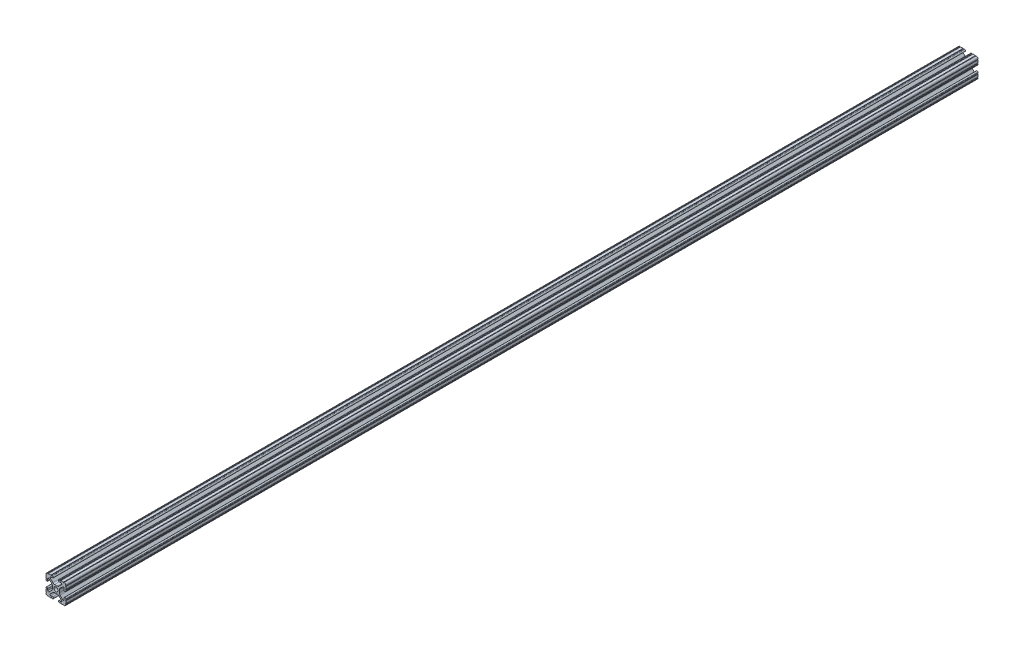
SolidWorks part; units mm, degrees
ref_plane "Front Plane" through (0, 0, 0) normal (0, 0, 1) x (1, 0, 0)
ref_plane "Top Plane" through (0, 0, 0) normal (0, 1, 0) x (1, 0, 0)
ref_plane "Right Plane" through (0, 0, 0) normal (1, 0, 0) x (0, 0, -1)
ref_plane "Plane1" through (0, 0, -2463.8) normal (0, 0, -1) x (-1, 0, 0)
sketch "Sketch1" plane through (0, 0, -2463.8) normal (0, 0, -1) x (-1, 0, 0)
  line L0 (12.7, -9.5504) -> (12.7, -6.3331)
  line L1 (12.7, -5.3171) -> (12.7, -4.3434)
  line L2 (10.4902, -4.3434) -> (10.4902, -6.4748)
  line L3 (8.7558, -7.1932) -> (5.4257, -3.8632)
  line L4 (4.4958, -1.6181) -> (4.4958, 1.6181)
  line L5 (5.4257, 3.8632) -> (8.7558, 7.1932)
  line L6 (10.4902, 6.4748) -> (10.4902, 4.3434)
  line L7 (12.7, 4.3434) -> (12.7, 5.3171)
  line L8 (12.7, 6.3331) -> (12.7, 9.5504)
  line L9 (9.5504, 12.7) -> (6.3331, 12.7)
  line L10 (5.3171, 12.7) -> (4.3434, 12.7)
  line L11 (4.3434, 10.4902) -> (6.4748, 10.4902)
  line L12 (7.1932, 8.7558) -> (3.8632, 5.4257)
  line L13 (1.6181, 4.4958) -> (-1.6181, 4.4958)
  line L14 (-3.8632, 5.4257) -> (-7.1932, 8.7558)
  line L15 (-6.4748, 10.4902) -> (-4.3434, 10.4902)
  line L16 (-4.3434, 12.7) -> (-5.3171, 12.7)
  line L17 (-6.3331, 12.7) -> (-9.5504, 12.7)
  line L18 (-12.7, 9.5504) -> (-12.7, 6.3331)
  line L19 (-12.7, 5.3171) -> (-12.7, 4.3434)
  line L20 (-10.4902, 4.3434) -> (-10.4902, 6.4748)
  line L21 (-8.7558, 7.1932) -> (-5.4257, 3.8632)
  line L22 (-4.4958, 1.6181) -> (-4.4958, -1.6181)
  line L23 (-5.4257, -3.8632) -> (-8.7558, -7.1932)
  line L24 (-10.4902, -6.4748) -> (-10.4902, -4.3434)
  line L25 (-12.7, -4.3434) -> (-12.7, -5.3171)
  line L26 (-12.7, -6.3331) -> (-12.7, -9.5504)
  line L27 (-9.5504, -12.7) -> (-6.3331, -12.7)
  line L28 (-5.3171, -12.7) -> (-4.3434, -12.7)
  line L29 (-4.3434, -10.4902) -> (-6.4748, -10.4902)
  line L30 (-7.1932, -8.7558) -> (-3.8632, -5.4257)
  line L31 (-1.6181, -4.4958) -> (1.6181, -4.4958)
  line L32 (3.8632, -5.4257) -> (7.1932, -8.7558)
  line L33 (6.4748, -10.4902) -> (4.3434, -10.4902)
  line L34 (4.3434, -12.7) -> (5.3171, -12.7)
  line L35 (6.3331, -12.7) -> (9.5504, -12.7)
  arc A0 (12.6998, -10.5664) -> (12.7, -9.5504) centre (12.7, -10.0584) cw
  arc A1 (12.7, -6.3331) -> (12.7, -5.3171) centre (12.7, -5.8251) cw
  arc A2 (12.7, -4.3434) -> (10.4902, -4.3434) centre (11.5951, -4.3434) ccw
  arc A3 (10.4902, -6.4748) -> (8.7558, -7.1932) centre (9.4742, -6.4748) cw
  arc A4 (5.4257, -3.8632) -> (4.4958, -1.6181) centre (7.6708, -1.6181) cw
  arc A5 (4.4958, 1.6181) -> (5.4257, 3.8632) centre (7.6708, 1.6181) cw
  arc A6 (8.7558, 7.1932) -> (10.4902, 6.4748) centre (9.4742, 6.4748) cw
  arc A7 (10.4902, 4.3434) -> (12.7, 4.3434) centre (11.5951, 4.3434) ccw
  arc A8 (12.7, 5.3171) -> (12.7, 6.3331) centre (12.7, 5.8251) cw
  arc A9 (12.7, 9.5504) -> (12.6998, 10.5664) centre (12.7, 10.0584) cw
  arc A10 (12.6998, 10.5664) -> (10.5664, 12.6998) centre (10.5918, 10.5918) ccw
  arc A11 (10.5664, 12.6998) -> (9.5504, 12.7) centre (10.0584, 12.7) cw
  arc A12 (6.3331, 12.7) -> (5.3171, 12.7) centre (5.8251, 12.7) cw
  arc A13 (4.3434, 12.7) -> (4.3434, 10.4902) centre (4.3434, 11.5951) ccw
  arc A14 (6.4748, 10.4902) -> (7.1932, 8.7558) centre (6.4748, 9.4742) cw
  arc A15 (3.8632, 5.4257) -> (1.6181, 4.4958) centre (1.6181, 7.6708) cw
  arc A16 (-1.6181, 4.4958) -> (-3.8632, 5.4257) centre (-1.6181, 7.6708) cw
  arc A17 (-7.1932, 8.7558) -> (-6.4748, 10.4902) centre (-6.4748, 9.4742) cw
  arc A18 (-4.3434, 10.4902) -> (-4.3434, 12.7) centre (-4.3434, 11.5951) ccw
  arc A19 (-5.3171, 12.7) -> (-6.3331, 12.7) centre (-5.8251, 12.7) cw
  arc A20 (-9.5504, 12.7) -> (-10.5664, 12.6998) centre (-10.0584, 12.7) cw
  arc A21 (-10.5664, 12.6998) -> (-12.6998, 10.5664) centre (-10.5918, 10.5918) ccw
  arc A22 (-12.6998, 10.5664) -> (-12.7, 9.5504) centre (-12.7, 10.0584) cw
  arc A23 (-12.7, 6.3331) -> (-12.7, 5.3171) centre (-12.7, 5.8251) cw
  arc A24 (-12.7, 4.3434) -> (-10.4902, 4.3434) centre (-11.5951, 4.3434) ccw
  arc A25 (-10.4902, 6.4748) -> (-8.7558, 7.1932) centre (-9.4742, 6.4748) cw
  arc A26 (-5.4257, 3.8632) -> (-4.4958, 1.6181) centre (-7.6708, 1.6181) cw
  arc A27 (-4.4958, -1.6181) -> (-5.4257, -3.8632) centre (-7.6708, -1.6181) cw
  arc A28 (-8.7558, -7.1932) -> (-10.4902, -6.4748) centre (-9.4742, -6.4748) cw
  arc A29 (-10.4902, -4.3434) -> (-12.7, -4.3434) centre (-11.5951, -4.3434) ccw
  arc A30 (-12.7, -5.3171) -> (-12.7, -6.3331) centre (-12.7, -5.8251) cw
  arc A31 (-12.7, -9.5504) -> (-12.6998, -10.5664) centre (-12.7, -10.0584) cw
  arc A32 (-12.6998, -10.5664) -> (-10.5664, -12.6998) centre (-10.5918, -10.5918) ccw
  arc A33 (-10.5664, -12.6998) -> (-9.5504, -12.7) centre (-10.0584, -12.7) cw
  arc A34 (-6.3331, -12.7) -> (-5.3171, -12.7) centre (-5.8251, -12.7) cw
  arc A35 (-4.3434, -12.7) -> (-4.3434, -10.4902) centre (-4.3434, -11.5951) ccw
  arc A36 (-6.4748, -10.4902) -> (-7.1932, -8.7558) centre (-6.4748, -9.4742) cw
  arc A37 (-3.8632, -5.4257) -> (-1.6181, -4.4958) centre (-1.6181, -7.6708) cw
  arc A38 (1.6181, -4.4958) -> (3.8632, -5.4257) centre (1.6181, -7.6708) cw
  arc A39 (7.1932, -8.7558) -> (6.4748, -10.4902) centre (6.4748, -9.4742) cw
  arc A40 (4.3434, -10.4902) -> (4.3434, -12.7) centre (4.3434, -11.5951) ccw
  arc A41 (5.3171, -12.7) -> (6.3331, -12.7) centre (5.8251, -12.7) cw
  arc A42 (9.5504, -12.7) -> (10.5664, -12.6998) centre (10.0584, -12.7) cw
  arc A43 (10.5664, -12.6998) -> (12.6998, -10.5664) centre (10.5918, -10.5918) ccw
  circle A44 centre (0, 0) radius 2.6035
extrude "Boss-Extrude1" add sketch "Sketch1" along normal blind 1168.4
